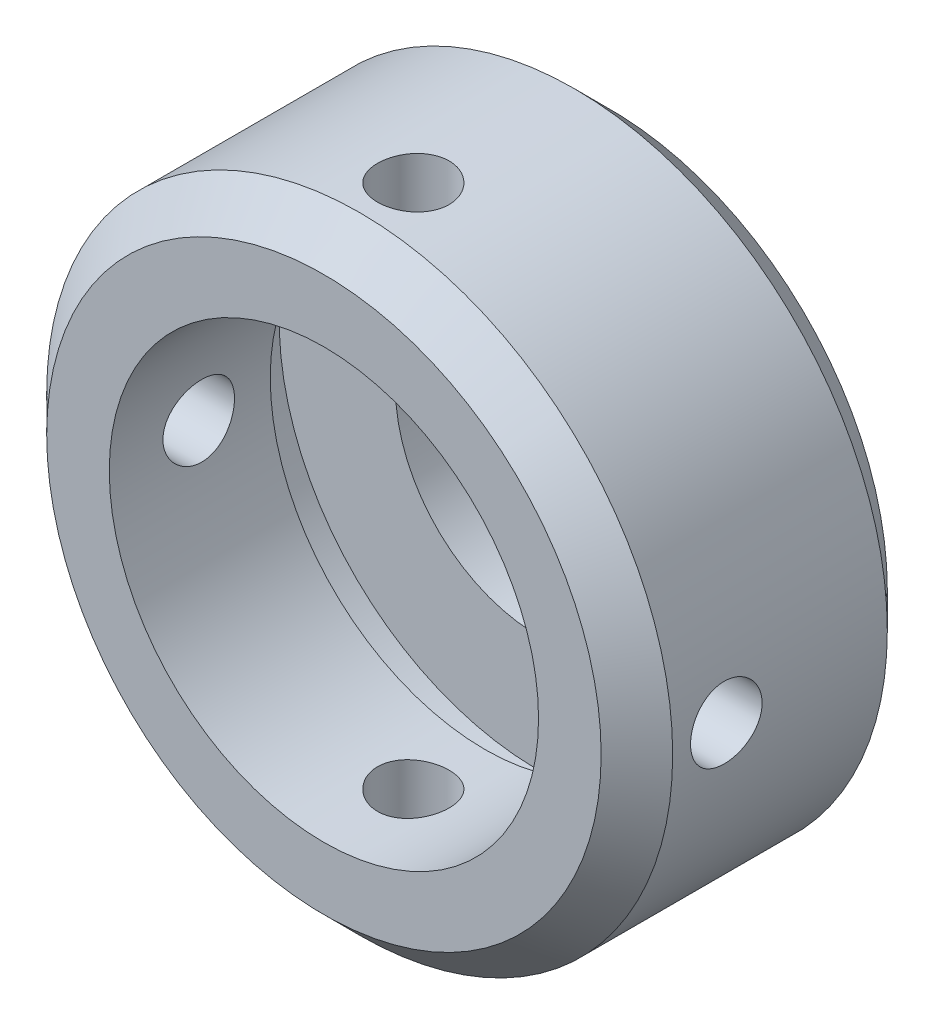
SolidWorks part; units mm, degrees
ref_plane "前视基准面" through (0, 0, 0) normal (0, 0, 1) x (1, 0, 0)
ref_plane "上视基准面" through (0, 0, 0) normal (0, 1, 0) x (1, 0, 0)
ref_plane "右视基准面" through (0, 0, 0) normal (1, 0, 0) x (0, 0, -1)
sketch "草图1" plane through (0, 0, 0) normal (0, 0, 1) x (1, 0, 0)
  circle A0 centre (0, 0) radius 17.5
  dimension "D1" = 35
extrude "凸台-拉伸1" add sketch "草图1" along normal blind 16
hole_wizard "M27 螺纹孔1" positions "草图2" profile "草图3" tap size "M27" standard "ISO"
sketch "草图2" plane through (0, 0, 16) normal (0, 0, 1) x (1, 0, 0)
  point P0 (0, 0)
sketch "草图3" plane through (0, 0, 16) normal (1, 0, 0) x (0, -1, 0)
  line L0 (0, 0) -> (0, 15.9282)
  line L1 (0, 15.9282) -> (12, 9)
  line L2 (12, 9) -> (12, 0)
  line L5 (12, 0) -> (0, 0)
  line L10 (0, 15.9282) -> (-12, 9) construction
  line L11 (0, -6.35) -> (0, 107.95) construction
  dimension "螺纹孔钻头直径" = 24
  dimension "螺纹孔钻头深度" = 9
  dimension "导头角度" = 120
cosmetic thread "孔螺蚊线1" parameters "D1"=9, "D2"=27
sketch "草图4" plane through (0, 0, 0) normal (0, 0, -1) x (-1, 0, 0)
  circle A1 centre (0, 0) radius 17.5
  circle A2 centre (0, 0) radius 17.5
  dimension "D1" = 0
extrude "凸台-拉伸2" add sketch "草图4" against normal blind 4
sketch "草图5" plane through (0, 0, 0) normal (1, 0, 0) x (0, 0, -1)
  line L0 (-7, 12) -> (-7, -12) construction
  line L1 (-7, 4.5) -> (-4, 4.5)
  line L2 (-7, 4.5) -> (-7, 14.5)
  line L3 (-7, 14.5) -> (-4, 14.5)
  line L4 (-4, 4.5) -> (-4, 14.5)
  dimension "D1" = 14.5
  dimension "D2" = 3
  dimension "D3" = 10
ref_axis "基准轴1" through (0, 0, 16) along (0, 0, -1)
revolve "切除-旋转1" cut sketch "草图5" angle 360 about axis through (0, 0, 16) along (0, 0, -1)
sketch "草图6" plane through (0, 0, 0) normal (1, 0, 0) x (0, 0, -1)
  line L0 (-16, 0) -> (0, 0) construction
  line L1 (-16, 17.5) -> (-16, -17.5) construction
  circle A0 centre (-11, 0) radius 2
  point P4 (0, 0)
  dimension "D1" = 4
  dimension "D2" = 5
extrude "切除-拉伸1" cut sketch "草图6" against normal through all
pattern_circular "阵列(圆周)1" count 4 over 360 about axis through (0, 0, 16) along (0, 0, -1) of "切除-拉伸1", "凸台-拉伸2"
sketch "草图7" plane through (0, 0, 0) normal (0, 0, -1) x (-1, 0, 0)
  circle A0 centre (0, 0) radius 8
  dimension "D1" = 16
extrude "切除-拉伸2" cut sketch "草图7" against normal through all
chamfer "倒角1" distance 2 angle 45 2 edges at (17.5, 0, 0) (17.5, 0, 16)
